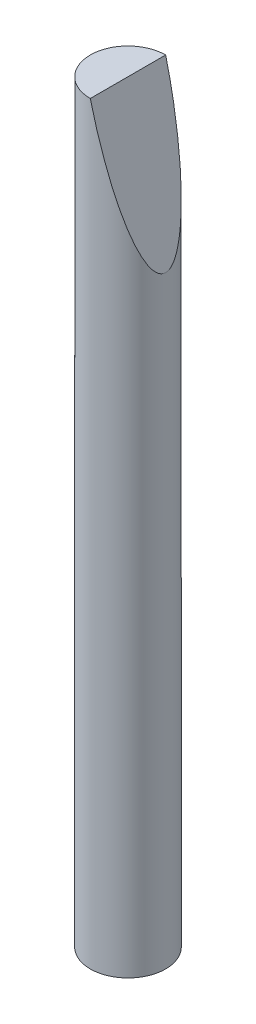
SolidWorks part; units mm, degrees
ref_plane "前视基准面" through (0, 0, 0) normal (0, 0, 1) x (1, 0, 0)
ref_plane "上视基准面" through (0, 0, 0) normal (0, 1, 0) x (1, 0, 0)
ref_plane "右视基准面" through (0, 0, 0) normal (1, 0, 0) x (0, 0, -1)
sketch "草图1" plane through (0, 0, 0) normal (0, 1, 0) x (1, 0, 0)
  circle A0 centre (0, 0) radius 1
  dimension "D1" = 2
extrude "凸台-拉伸1" add sketch "草图1" along normal blind 20
sketch "草图2" plane through (0, 0, 0) normal (0, 0, 1) x (1, 0, 0)
  line L1 (1, 0) -> (1, 20) construction
  line L2 (1, 16) -> (1, 20)
  line L4 (1, 16) -> (0, 20)
  line L5 (0, 20) -> (1, 20)
  point P0 (0, 20)
  dimension "D1" = 4
  dimension "D2" = 1
extrude "切除-拉伸1" cut sketch "草图2" against normal through all and the other way through all contours L5 L2 L4
